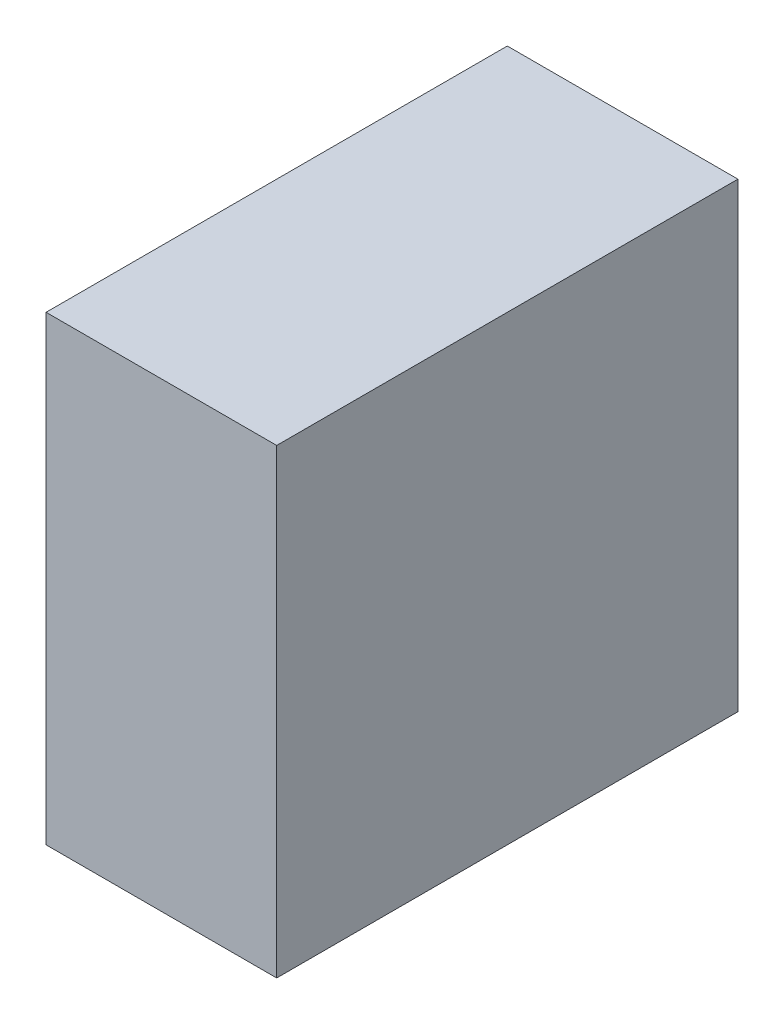
SolidWorks part; units mm, degrees
ref_plane "Front Plane" through (0, 0, 0) normal (0, 0, 1) x (1, 0, 0)
ref_plane "Top Plane" through (0, 0, 0) normal (0, 1, 0) x (1, 0, 0)
ref_plane "Right Plane" through (0, 0, 0) normal (1, 0, 0) x (0, 0, -1)
sketch "Sketch1" plane through (0, 0, 0) normal (0, 0, 1) x (1, 0, 0)
  line L1 (-12.5, 25) -> (12.5, 25)
  line L2 (-12.5, 25) -> (-12.5, -25)
  line L3 (-12.5, -25) -> (12.5, -25)
  line L4 (12.5, 25) -> (12.5, -25)
  line L5 (-12.5, 25) -> (12.5, -25) construction
  line L6 (-12.5, -25) -> (12.5, 25) construction
  point P0 (0, 0)
  dimension "D1" = 50
  dimension "D2" = 25
extrude "Boss-Extrude1" add sketch "Sketch1" along normal blind 50
